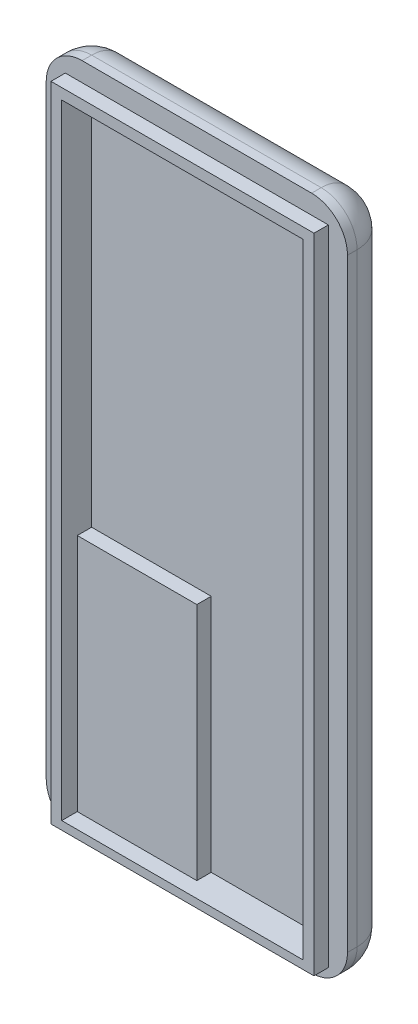
SolidWorks part; units mm, degrees
ref_plane "Спереди" through (0, 0, 0) normal (0, 0, 1) x (1, 0, 0)
ref_plane "Сверху" through (0, 0, 0) normal (0, 1, 0) x (1, 0, 0)
ref_plane "Справа" through (0, 0, 0) normal (1, 0, 0) x (0, 0, -1)
sketch "Эскиз1" plane through (0, 0, 0) normal (0, 0, 1) x (1, 0, 0)
  line L1 (0, 0) -> (25.2, 0)
  line L2 (0, 0) -> (0, 56.5)
  line L3 (0, 56.5) -> (25.2, 56.5)
  line L4 (25.2, 0) -> (25.2, 56.5)
  dimension "D1" = 56.5
  dimension "D2" = 25.2
extrude "Бобышка-Вытянуть1" add sketch "Эскиз1" along normal blind 5
sketch "Эскиз2" plane through (0, 0, 5) normal (0, 0, 1) x (1, 0, 0)
  line L1 (0, 56.5) -> (25.2, 56.5)
  line L2 (0, 56.5) -> (0, 0)
  line L3 (0, 0) -> (25.2, 0)
  line L4 (25.2, 56.5) -> (25.2, 0)
  line L5 (1.6, 54.9) -> (23.6, 54.9)
  line L6 (1.6, 54.9) -> (1.6, 1.1)
  line L7 (1.6, 1.1) -> (23.6, 1.1)
  line L8 (23.6, 54.9) -> (23.6, 1.1)
  dimension "D1" = 53.8
  dimension "D2" = 22
  dimension "D3" = 1.6
  dimension "D4" = 1.1
  dimension "D5" = 1.6
extrude "Вырез-Вытянуть1" cut sketch "Эскиз2" against normal blind 1.3
sketch "Эскиз3" plane through (0, 0, 5) normal (0, 0, 1) x (1, 0, 0)
  line L0 (1.6, 54.9) -> (1.6, 1.1) construction
  line L1 (2.5, 54) -> (22.7, 54)
  line L2 (2.5, 54) -> (2.5, 1.8)
  line L3 (2.5, 1.8) -> (22.7, 1.8)
  line L4 (22.7, 54) -> (22.7, 1.8)
  line L5 (23.6, 54.9) -> (1.6, 54.9) construction
  line L6 (23.6, 1.1) -> (23.6, 54.9) construction
  line L7 (1.6, 1.1) -> (23.6, 1.1) construction
  dimension "D1" = 0.9
  dimension "D2" = 0.9
  dimension "D3" = 0.9
  dimension "D4" = 0.7
extrude "Вырез-Вытянуть2" cut sketch "Эскиз3" against normal blind 2.6
sketch "Эскиз4" plane through (1.6, 0, 0) normal (-1, 0, 0) x (0, 0, 1)
  line L5 (3.7, 1.1) -> (5, 1.1) construction
  line L6 (5, 54.9) -> (4.9, 54.9)
  line L7 (5, 54.9) -> (5, 1.1)
  line L8 (5, 1.1) -> (4.9, 1.1)
  line L9 (4.9, 54.9) -> (4.9, 1.1)
  dimension "D1" = 0.1
extrude "Вырез-Вытянуть3" cut sketch "Эскиз4" against normal through all
sketch "Эскиз5" plane through (0, 0, 0) normal (0, 0, -1) x (-1, 0, 0)
  line L1 (-25.2, 56.5) -> (0, 56.5)
  line L2 (-25.2, 56.5) -> (-25.2, 0)
  line L3 (-25.2, 0) -> (0, 0)
  line L4 (0, 56.5) -> (0, 0)
extrude "Бобышка-Вытянуть2" add sketch "Эскиз5" along normal blind 0.1
sketch "Эскиз6" plane through (0, 0, 2.4) normal (0, 0, 1) x (1, 0, 0)
  line L1 (2.5, 1.8) -> (12.5, 1.8)
  line L2 (2.5, 1.8) -> (2.5, 21.8)
  line L3 (2.5, 21.8) -> (12.5, 21.8)
  line L4 (12.5, 1.8) -> (12.5, 21.8)
  dimension "D1" = 10
  dimension "D2" = 20
extrude "Бобышка-Вытянуть3" add sketch "Эскиз6" along normal blind 1.2
fillet "Скругление1" radius 3 8 edges at (12.6, 56.5, -0.1) (0, 28.25, -0.1) (12.6, 0, -0.1) (25.2, 28.25, -0.1) (25.2, 56.5, 1.8) (0, 56.5, 1.8) (0, 0, 1.8) (25.2, 0, 1.8)
